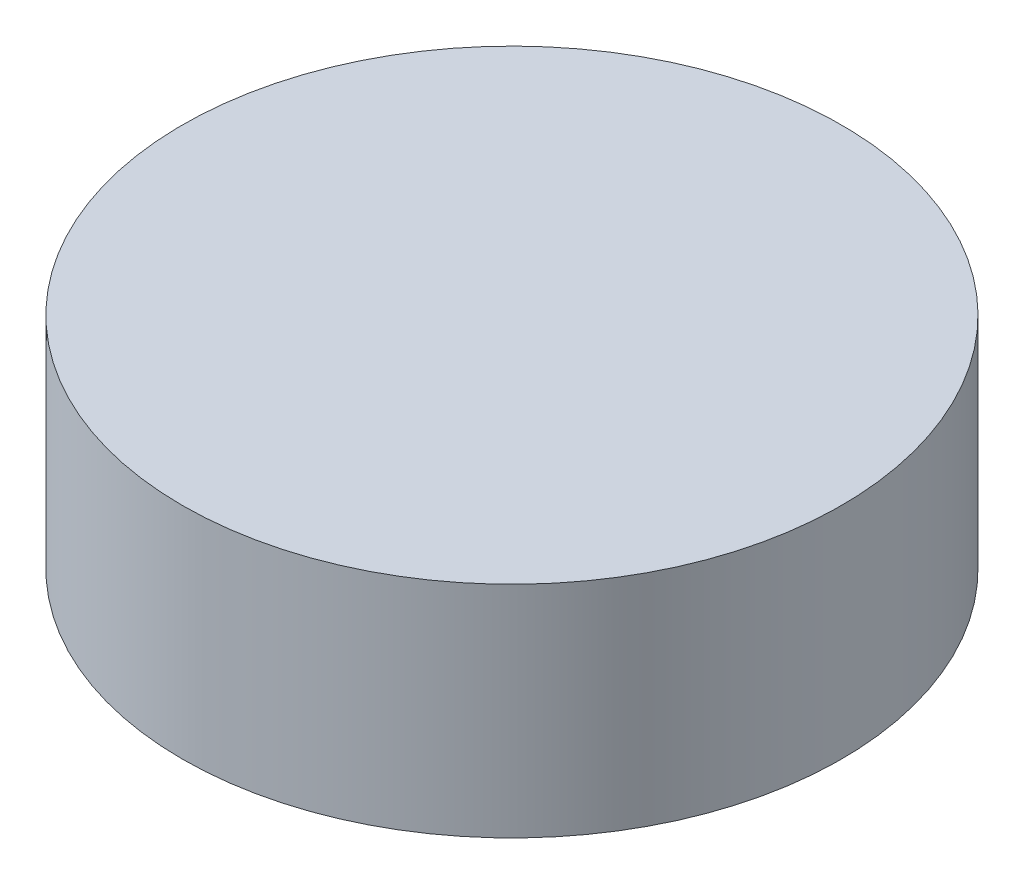
SolidWorks part; units mm, degrees
ref_plane "Front Plane" through (0, 0, 0) normal (0, 0, 1) x (1, 0, 0)
ref_plane "Top Plane" through (0, 0, 0) normal (0, 1, 0) x (1, 0, 0)
ref_plane "Right Plane" through (0, 0, 0) normal (1, 0, 0) x (0, 0, -1)
sketch "Sketch1" plane through (0, 0, 0) normal (0, 1, 0) x (1, 0, 0)
  circle A0 centre (0, 0) radius 30
  dimension "D1" = 60
extrude "Boss-Extrude1" add sketch "Sketch1" along normal mid plane 20
sketch "Sketch2" plane through (0, -10, 0) normal (0, -1, 0) x (1, 0, 0)
  circle A0 centre (0, 0) radius 23
  circle A1 centre (0, 0) radius 30 construction
  dimension "D1" = 7
extrude "Cut-Extrude1" cut sketch "Sketch2" against normal blind 15
